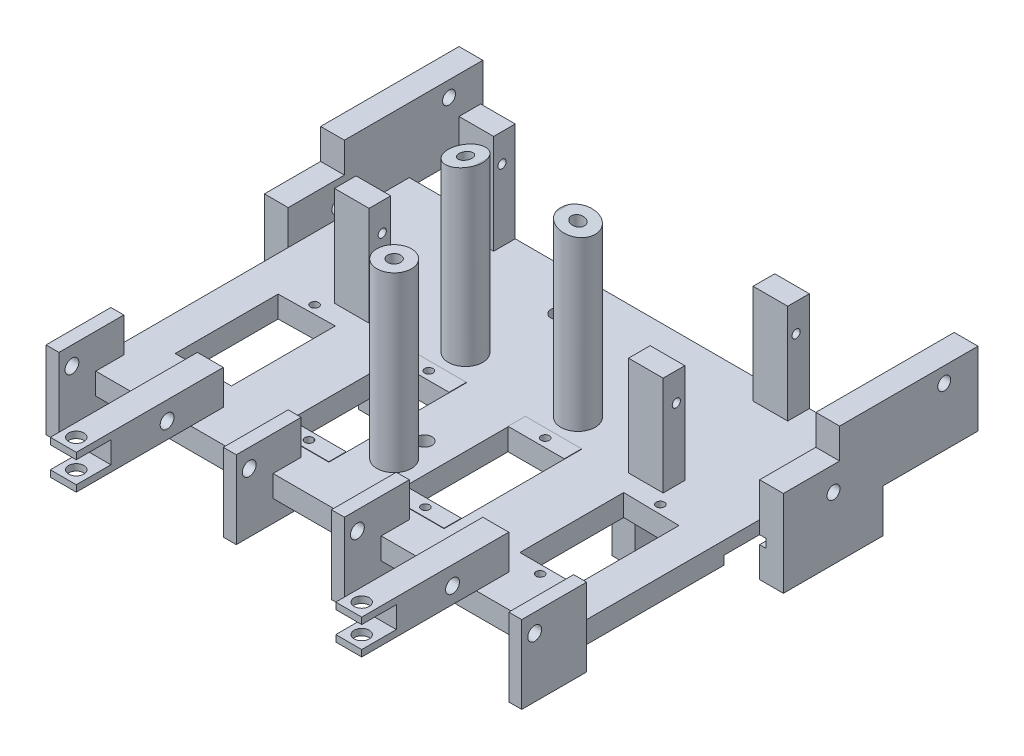
SolidWorks part; units mm, degrees
material "PMMA"
ref_plane "前视基准面" through (0, 0, 0) normal (0, 0, 1) x (1, 0, 0)
ref_plane "上视基准面" through (0, 0, 0) normal (0, 1, 0) x (1, 0, 0)
ref_plane "右视基准面" through (0, 0, 0) normal (1, 0, 0) x (0, 0, -1)
sketch "草图1" plane through (0, 0, 0) normal (0, 1, 0) x (1, 0, 0)
  line L1 (-54.5, 37.5) -> (54.5, 37.5)
  line L2 (-54.5, 37.5) -> (-54.5, -37.5)
  line L3 (-54.5, -37.5) -> (54.5, -37.5)
  line L4 (54.5, 37.5) -> (54.5, -37.5)
  line L5 (-54.5, 37.5) -> (54.5, -37.5) construction
  line L6 (-54.5, -37.5) -> (54.5, 37.5) construction
  point P0 (0, 0)
  dimension "D1" = 109
  dimension "D2" = 75
extrude "凸台-拉伸1" add sketch "草图1" along normal blind 5
sketch "草图4" plane through (0, 5, 0) normal (0, 1, 0) x (1, 0, 0)
  line L1 (-52.5, 9.5) -> (52.5, 9.5)
  line L2 (-52.5, 9.5) -> (-52.5, 37.5)
  line L3 (-52.5, 37.5) -> (52.5, 37.5)
  line L4 (52.5, 9.5) -> (52.5, 37.5)
  line L5 (-52.5, 9.5) -> (52.5, 37.5) construction
  line L6 (-52.5, 37.5) -> (52.5, 9.5) construction
  line L7 (-54.5, -37.5) -> (54.5, -37.5) construction
  point P0 (0, 23.5)
  dimension "D1" = 105
  dimension "D2" = 28
  dimension "D3" = 75
extrude "凸台-拉伸4" add sketch "草图4" against normal blind 5
sketch "草图5" plane through (-54.5, 0, 0) normal (-1, 0, 0) x (0, 0, 1)
  line L1 (-9.5, 13) -> (-32.5, 13)
  line L2 (-9.5, 13) -> (-9.5, -7)
  line L3 (-9.5, -7) -> (-32.5, -7)
  line L4 (-32.5, 13) -> (-32.5, -7)
  line L6 (-37.5, 5) -> (-37.5, 0) construction
  line L7 (-37.5, 5) -> (37.5, 5) construction
  dimension "D1" = 5
  dimension "D2" = 23
  dimension "D3" = 20
  dimension "D4" = 8
extrude "凸台-拉伸5" add sketch "草图5" along normal blind 5.5
sketch "草图6" plane through (-54.5, 0, 0) normal (-1, 0, 0) x (0, 0, 1)
  line L0 (-37.5, 5) -> (-32.5, 5) construction
  line L1 (-54.5, 20) -> (-22.5, 20)
  line L2 (-54.5, 20) -> (-54.5, 3)
  line L3 (-54.5, 3) -> (-22.5, 3)
  line L4 (-22.5, 20) -> (-22.5, 3)
  line L5 (-37.5, 5) -> (-37.5, 0) construction
  dimension "D1" = 15
  dimension "D2" = 17
  dimension "D3" = 32
  dimension "D4" = 17
extrude "凸台-拉伸6" add sketch "草图6" along normal blind 5.5
sketch "草图8" plane through (0, 5, 0) normal (0, 1, 0) x (1, 0, 0)
  line L0 (54.5, 37.5) -> (-54.5, 37.5) construction
  line L1 (-38, 37.5) -> (-30, 37.5)
  line L2 (-38, 37.5) -> (-38, 32.5)
  line L3 (-38, 32.5) -> (-30, 32.5)
  line L4 (-30, 37.5) -> (-30, 32.5)
  line L6 (-38, 8.7) -> (-30, 8.7)
  line L7 (-38, 8.7) -> (-38, 3.7)
  line L8 (-38, 3.7) -> (-30, 3.7)
  line L9 (-30, 8.7) -> (-30, 3.7)
  dimension "D1" = 23.8
  dimension "D2" = 38
  dimension "D3" = 8
  dimension "D4" = 5
  dimension "D5" = 5
extrude "凸台-拉伸7" add sketch "草图8" along normal blind 23
sketch "草图9" plane through (0, 5, 0) normal (0, 1, 0) x (1, 0, 0)
  line L1 (-14, -31) -> (-11, -31)
  line L2 (-14, -31) -> (-14, -46)
  line L3 (-14, -46) -> (-11, -46)
  line L4 (-11, -31) -> (-11, -46)
  dimension "D1" = 14
  dimension "D2" = 3
  dimension "D3" = 15
  dimension "D4" = 46
extrude "凸台-拉伸8" add sketch "草图9" along normal blind 8 and the other way blind 10
sketch "草图10" plane through (0, 5, 0) normal (0, 1, 0) x (1, 0, 0)
  line L0 (-14, -31) -> (-14, -46) construction
  line L1 (-55, -31) -> (-52, -31)
  line L2 (-55, -31) -> (-55, -46)
  line L3 (-55, -46) -> (-52, -46)
  line L4 (-52, -31) -> (-52, -46)
  line L6 (-11, -31) -> (-14, -31) construction
  line L7 (-14, -46) -> (-11, -46) construction
  dimension "D1" = 38
extrude "凸台-拉伸9" add sketch "草图10" along normal blind 8 and the other way blind 10
sketch "草图11" plane through (0, 5, 0) normal (0, 1, 0) x (1, 0, 0)
  line L1 (-36, -30) -> (-30, -30)
  line L2 (-36, -30) -> (-36, -64)
  line L3 (-36, -64) -> (-30, -64)
  line L4 (-30, -30) -> (-30, -64)
  dimension "D1" = 6
  dimension "D2" = 34
  dimension "D3" = 64
  dimension "D4" = 30
extrude "凸台-拉伸10" add sketch "草图11" along normal blind 8
sketch "草图12" plane through (0, 5, 0) normal (0, 1, 0) x (1, 0, 0)
  circle A0 centre (-13, 9) radius 4
  dimension "D1" = 13
  dimension "D2" = 9
  dimension "D3" = 8
extrude "凸台-拉伸11" add sketch "草图12" along normal blind 40
sketch "草图19" plane through (-38, 0, 0) normal (-1, 0, 0) x (0, 0, 1)
  line L1 (-8.7, 28) -> (-8.7, 5) construction
  line L2 (-8.7, 28) -> (-3.7, 28) construction
  line L3 (-32.5, 28) -> (-32.5, 5) construction
  circle A0 centre (-6.75, 21.5) radius 0.95
  circle A1 centre (-34.45, 21.5) radius 0.95
  dimension "D1" = 6.5
  dimension "D2" = 1.95
  dimension "D3" = 1.9
  dimension "D4" = 27.7
  dimension "D5" = 1.9
  dimension "D6" = 1.95
extrude "切除-拉伸8" cut sketch "草图19" against normal up to next
sketch "草图25" plane through (0, 5, 0) normal (0, 1, 0) x (1, 0, 0)
  circle A0 centre (0, -20.5) radius 4
  circle A1 centre (-13, 9) radius 4 construction
  dimension "D1" = 20.5
extrude "凸台-拉伸14" add sketch "草图25" along normal blind 40
sketch "草图26" plane through (0, 0, 0) normal (0, 0, 1) x (1, 0, 0)
  line L0 (-17, 45) -> (-17, 43.644)
  line L1 (-17, 45) -> (-17, 5) construction
  line L2 (-17, 43.644) -> (-9.31, 45)
  line L3 (-9, 45) -> (-17, 45) construction
  line L4 (-9.31, 45) -> (-17, 45)
  dimension "D1" = 10
  dimension "D2" = 0.31
extrude "切除-拉伸14" cut sketch "草图26" against normal blind 36
sketch "草图28" plane through (0, 0, 64) normal (0, 0, 1) x (1, 0, 0)
  line L0 (-36, 13) -> (-36, 5) construction
  line L1 (-36, 11.5) -> (-30, 11.5)
  line L2 (-36, 11.5) -> (-36, 6.5)
  line L3 (-36, 6.5) -> (-30, 6.5)
  line L4 (-30, 11.5) -> (-30, 6.5)
  line L5 (-30, 13) -> (-30, 5) construction
  line L6 (-36, 13) -> (-30, 13) construction
  dimension "D1" = 1.5
  dimension "D2" = 5
extrude "切除-拉伸16" cut sketch "草图28" against normal blind 8
sketch "草图29" plane through (0, 13, 0) normal (0, 1, 0) x (1, 0, 0)
  line L0 (-36, -64) -> (-30, -64) construction
  circle A0 centre (-33, -61) radius 1.75
  point P5 (-33, -64)
  dimension "D1" = 3
  dimension "D2" = 3.5
extrude "切除-拉伸17" cut sketch "草图29" against normal blind 8
sketch "草图30" plane through (-55, 0, 0) normal (-1, 0, 0) x (0, 0, 1)
  line L0 (31, 5) -> (37.5, 5) construction
  circle A0 centre (43, 8.75) radius 1.6
  dimension "D1" = 43
  dimension "D2" = 3.75
  dimension "D3" = 3.2
extrude "切除-拉伸18" cut sketch "草图30" against normal blind 48
sketch "草图31" plane through (0, 5, 0) normal (0, 1, 0) x (1, 0, 0)
  circle A0 centre (0, -13.5) radius 1.75
  circle A1 centre (-10, 27.5) radius 1.75
  circle A2 centre (10, 27.5) radius 1.75
  dimension "D1" = 20
  dimension "D2" = 10
  dimension "D3" = 27.5
  dimension "D4" = 3.5
  dimension "D5" = 3.5
  dimension "D7" = 3.5
  dimension "D6" = 13.5
extrude "切除-拉伸19" cut sketch "草图31" against normal blind 20
sketch "草图34" plane through (-55, 0, 0) normal (-1, 0, 0) x (0, 0, 1)
  line L0 (46, -5) -> (46, 13) construction
  line L1 (46, 5) -> (43, 5)
  line L2 (46, 5) -> (46, -5)
  line L3 (46, -5) -> (43, -5)
  line L4 (43, 5) -> (43, -5)
  line L5 (37.5, 5) -> (64, 5) construction
  line L6 (31, -5) -> (46, -5) construction
  dimension "D1" = 3
sketch "草图35" plane through (-60, 0, 0) normal (-1, 0, 0) x (0, 0, 1)
  circle A0 centre (-46.6884, 16.4527) radius 1.5
  circle A1 centre (-21.0894, 7.4378) radius 1.5
  dimension "D1" = 3
  dimension "D2" = 3
extrude "切除-拉伸23" cut sketch "草图35" against normal blind 15
sketch "草图36" plane through (0, 5, 0) normal (0, 1, 0) x (1, 0, 0)
  line L0 (-13.4508, 4.0639) -> (-13.4508, -27.9765) construction
  line L1 (-19.8158, -0.9819) -> (-6.8158, -0.9819)
  line L2 (-19.8158, -0.9819) -> (-19.8158, -24.7819)
  line L3 (-19.8158, -24.7819) -> (-6.8158, -24.7819)
  line L4 (-6.8158, -0.9819) -> (-6.8158, -24.7819)
  line L5 (-33.3471, -0.7664) -> (-33.3471, -24.7819)
  line L6 (-39.9809, 4.2721) -> (-39.9809, -27.7684) construction
  line L7 (-46.3459, -24.7819) -> (-33.3471, -24.7819)
  line L8 (-46.3453, -0.9819) -> (-46.3459, -24.7819)
  line L9 (-46.3453, -0.9819) -> (-33.3471, -0.7664)
  circle A0 centre (-13.4508, 0.9681) radius 0.95
  circle A1 centre (-13.4508, -26.7319) radius 0.95
  circle A2 centre (-39.9809, -26.7319) radius 0.95
  circle A3 centre (-39.98, 1.0739) radius 0.95
  dimension "D3" = 1.9
  dimension "D4" = 1.9
  dimension "D9" = 1.9
  dimension "D10" = 1.9
  dimension "D1" = 23.8
  dimension "D2" = 13
  dimension "D5" = 1.95
  dimension "D6" = 1.95
  dimension "D7" = 23.8
  dimension "D8" = 13
  dimension "D11" = 1.95
  dimension "D12" = 1.95
extrude "切除-拉伸24" cut sketch "草图36" against normal blind 7
sketch "草图37" plane through (0, 0, 0) normal (0, -1, 0) x (1, 0, 0)
  line L1 (-26.6386, -37.023) -> (-32.6386, -37.023)
  line L2 (-26.6386, -37.023) -> (-26.6386, -32.023)
  line L3 (-26.6386, -32.023) -> (-32.6386, -32.023)
  line L4 (-32.6386, -37.023) -> (-32.6386, -32.023)
  line L5 (-26.6386, -8.223) -> (-31.945, -8.223)
  line L6 (-26.6386, -8.223) -> (-26.6386, -3.223)
  line L7 (-26.6386, -3.223) -> (-31.945, -3.223)
  line L8 (-31.945, -8.223) -> (-31.945, -3.223)
  dimension "D1" = 23.8
  dimension "D2" = 6
  dimension "D3" = 5
  dimension "D4" = 5
extrude "凸台-拉伸15" add sketch "草图37" along normal blind 13
sketch "草图38" plane through (-32.6386, 0, 0) normal (-1, 0, 0) x (0, 0, 1)
  line L0 (-32.023, -13) -> (-32.023, 0) construction
  line L1 (-37.5, 0) -> (-32.5, 0) construction
  line L3 (-20.123, 2.1642) -> (-20.123, -15.8009) construction
  circle A0 centre (-33.973, -4.5) radius 0.95
  circle A1 centre (-6.273, -4.5) radius 0.95
  dimension "D1" = 1.9
  dimension "D2" = 1.95
  dimension "D3" = 4.5
  dimension "D4" = 11.9
extrude "切除-拉伸25" cut sketch "草图38" against normal blind 13
sketch "草图43" plane through (0, 0, 0) normal (0, -1, 0) x (1, 0, 0)
  line L0 (54.5, -37.5) -> (-54.5, -37.5) construction
  line L1 (-55.945, -1.223) -> (-18.6386, -1.223)
  line L2 (-55.945, -1.223) -> (-55.945, -37.5)
  line L3 (-55.945, -37.5) -> (-18.6386, -37.5)
  line L4 (-18.6386, -1.223) -> (-18.6386, -37.5)
  line L5 (-26.6386, -3.223) -> (-31.945, -3.223) construction
  line L6 (-26.6386, -8.223) -> (-26.6386, -3.223) construction
  line L7 (-26.6386, -3.223) -> (-31.945, -3.223) construction
  line L8 (-31.945, -3.223) -> (-31.945, -8.223) construction
  line L9 (-31.945, -8.223) -> (-26.6386, -8.223) construction
  line L10 (-26.6386, -37.023) -> (-26.6386, -32.023) construction
  line L11 (-26.6386, -32.023) -> (-32.6386, -32.023) construction
  line L12 (-32.6386, -32.023) -> (-32.6386, -37.023) construction
  line L13 (-32.6386, -37.023) -> (-26.6386, -37.023) construction
  line L14 (-26.6386, -8.223) -> (-26.6386, -3.223)
  line L15 (-26.6386, -3.223) -> (-31.945, -3.223)
  line L16 (-31.945, -3.223) -> (-31.945, -8.223)
  line L17 (-31.945, -8.223) -> (-26.6386, -8.223)
  line L18 (-26.6386, -37.023) -> (-26.6386, -32.023)
  line L19 (-26.6386, -32.023) -> (-32.6386, -32.023)
  line L20 (-32.6386, -32.023) -> (-32.6386, -37.023)
  line L21 (-32.6386, -37.023) -> (-26.6386, -37.023)
  dimension "D1" = 2
  dimension "D2" = 8
  dimension "D3" = 24
extrude "切除-拉伸28" cut sketch "草图43" against normal blind 2
sketch "草图41" plane through (0, 5, 0) normal (0, 1, 0) x (1, 0, 0)
  line L0 (-19.8158, -0.9819) -> (-19.8158, -24.7819) construction
  line L1 (-6.8158, -0.9819) -> (-19.8158, -0.9819)
  line L2 (-6.8158, -0.9819) -> (-6.8158, 3.0181)
  line L3 (-6.8158, 3.0181) -> (-19.8158, 3.0181)
  line L4 (-19.8158, -0.9819) -> (-19.8158, 3.0181)
  line L5 (-6.8158, -24.7819) -> (-6.8158, -0.9819) construction
  line L6 (-19.8158, -24.7819) -> (-6.8158, -24.7819)
  line L7 (-19.8158, -24.7819) -> (-19.8158, -28.7819)
  line L8 (-19.8158, -28.7819) -> (-6.8158, -28.7819)
  line L9 (-6.8158, -24.7819) -> (-6.8158, -28.7819)
  circle A0 centre (-13.4508, 0.9681) radius 0.95
  circle A1 centre (-13.4508, -26.7319) radius 0.95
  dimension "D3" = 1.9
  dimension "D4" = 1.9
  dimension "D1" = 4
  dimension "D2" = 4
extrude "凸台-拉伸16" add sketch "草图41" along normal blind 0.1
sketch "草图39" plane through (0, 5, 0) normal (0, 1, 0) x (1, 0, 0)
  circle A0 centre (-13, 9) radius 1.5
  circle A1 centre (0, -20.5) radius 1.5
  dimension "D1" = 3
  dimension "D2" = 3
extrude "切除-拉伸26" cut sketch "草图39" against normal blind 13 and the other way blind 42
mirror "镜向1" about plane through (0, 0, 0) normal (1, 0, 0) of "凸台-拉伸5", "凸台-拉伸6", "凸台-拉伸7", "凸台-拉伸8", "凸台-拉伸9", "凸台-拉伸10", "凸台-拉伸11", "切除-拉伸8", "切除-拉伸14", "切除-拉伸16", "切除-拉伸17", "切除-拉伸18", "切除-拉伸23", "切除-拉伸24", "凸台-拉伸15", "切除-拉伸25", "切除-拉伸28", "凸台-拉伸16", "切除-拉伸26"
